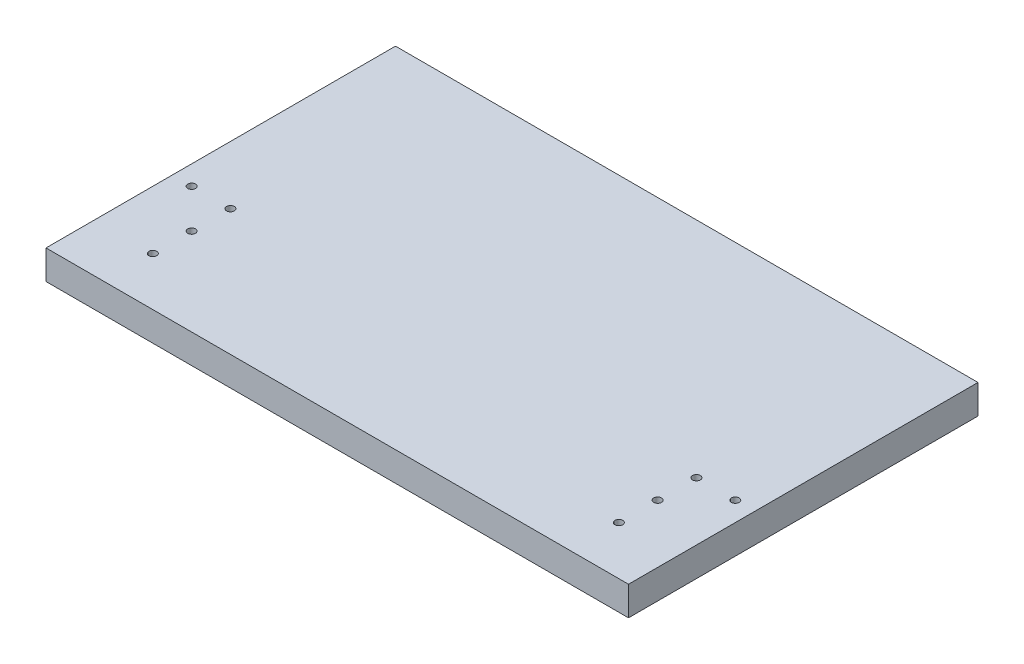
SolidWorks part; units mm, degrees
ref_plane "Alzado" through (0, 0, 0) normal (0, 0, 1) x (1, 0, 0)
ref_plane "Planta" through (0, 0, 0) normal (0, 1, 0) x (1, 0, 0)
ref_plane "Vista lateral" through (0, 0, 0) normal (1, 0, 0) x (0, 0, -1)
sketch "Croquis1" plane through (0, 0, 0) normal (0, 1, 0) x (1, 0, 0)
  line L1 (-150, -90) -> (150, -90)
  line L2 (-150, -90) -> (-150, 90)
  line L3 (-150, 90) -> (150, 90)
  line L4 (150, -90) -> (150, 90)
  line L5 (-150, -90) -> (150, 90) construction
  line L6 (-150, 90) -> (150, -90) construction
  point P0 (0, 0)
  dimension "D1" = 300
  dimension "D2" = 180
extrude "Saliente-Extruir1" add sketch "Croquis1" along normal blind 15
sketch "Croquis2" plane through (0, 15, 0) normal (0, 1, 0) x (1, 0, 0)
  line L1 (-150, -90) -> (150, -90) construction
  line L2 (-150, 90) -> (-150, -90) construction
  line L3 (150, -90) -> (150, 90) construction
  circle A0 centre (-120, -65) radius 2
  circle A1 centre (-120, -45) radius 2
  circle A2 centre (120, -65) radius 2
  circle A3 centre (120, -45) radius 2
  circle A4 centre (-140, -25) radius 2
  circle A5 centre (-120, -25) radius 2
  circle A6 centre (120, -25) radius 2
  circle A7 centre (140, -25) radius 2
  dimension "D1" = 25
  dimension "D2" = 0
  dimension "D3" = 25
  dimension "D4" = 0
  dimension "D7" = 10
  dimension "D8" = 20
  dimension "D9" = 30
  dimension "D10" = 10
  dimension "D5" = 30
  dimension "D6" = 30
  dimension "D11" = 65
  dimension "D12" = 0
  dimension "D13" = 65
  dimension "D14" = 0
  dimension "D15" = 45
  dimension "D16" = 45
extrude "Cortar-Extruir1" cut sketch "Croquis2" against normal blind 10
sketch "Croquis3" plane through (0, 0, 0) normal (0, -1, 0) x (1, 0, 0)
  line L0 (150, -90) -> (-150, -90) construction
  line L1 (150, 90) -> (150, -90) construction
  circle A0 centre (140, -65) radius 2
  point P6 (0, 0)
  dimension "D1" = 25
  dimension "D2" = 10
extrude "Cortar-Extruir2" cut sketch "Croquis3" against normal blind 10
